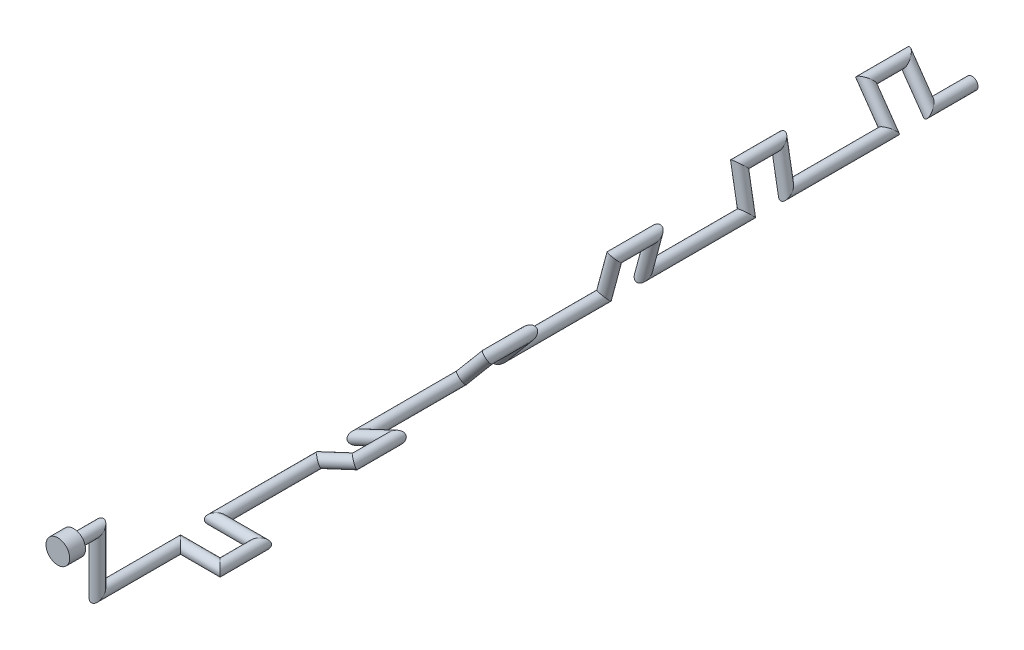
SolidWorks part; units mm, degrees
ref_plane "Front Plane" through (0, 0, 0) normal (0, 0, 1) x (1, 0, 0)
ref_plane "Top Plane" through (0, 0, 0) normal (0, 1, 0) x (1, 0, 0)
ref_plane "Right Plane" through (0, 0, 0) normal (1, 0, 0) x (0, 0, -1)
sketch "Sketch3" plane through (0, 0, 0) normal (0, 0, 1) x (1, 0, 0)
  circle A0 centre (0, 177.8) radius 38.1
  dimension "D1" = 76.2
  dimension "D2" = 177.8
extrude "Boss-Extrude2" add sketch "Sketch3" along normal blind 50.8
sketch "Sketch4" plane through (0, 0, 0) normal (0, 0, -1) x (-1, 0, 0)
  circle A0 centre (0, 177.8) radius 19.05
  dimension "D1" = 38.1
sketch3d "3DSketch1"
  line L0 (0, 177.8, 0) -> (0, 177.8, -76.2)
  line L1 (0, 177.8, 50.8) -> (0, 177.8, 0) construction
  line L2 (0, 0, -76.2) -> (0, 0, -177.8)
  line L4 (0, 177.8, -76.2) -> (0, 0, -76.2)
  dimension "D1" = 76.2
  dimension "D2" = 101.6
sweep "Sweep1" add profiles "Sketch4" path "3DSketch1"
fillet "Fillet1" radius 12.7 1 edges at (-19.05, 177.8, 0)
sketch3d "3DSketch2"
  line L0 (0, 0, -177.8) -> (0, 0, -342.9)
  line L1 (0, 0, -95.25) -> (0, 0, -177.8) construction
  line L2 (0, 0, -342.9) -> (127, 0, -342.9)
  line L3 (0, 0, -342.9) -> (156.6393, 0, -342.9) construction
  line L4 (127, 0, -342.9) -> (127, 0, -469.9)
  line L8 (127, 0, -469.9) -> (-12.7, 0, -469.9)
  line L9 (-12.7, 0, -469.9) -> (-12.7, 0, -800.1)
  line L14 (-12.7, 0, -800.1) -> (102.4011, 53.6699, -800.6318)
  line L15 (-12.7, 0, -800.1) -> (94.1188, 0, -800.1) construction
  line L16 (102.4011, 53.6699, -800.6318) -> (102.4011, 53.6699, -927.6318)
  line L18 (-12.7, 0, -800.1) -> (-12.7, 0, -4505.9984) construction
  line L20 (-12.7, 0, -927.1) -> (102.4011, 53.6699, -927.6318)
  line L21 (-12.7, 0, -927.1) -> (83.0144, 0, -927.1) construction
  line L22 (-12.7, 0, -927.1) -> (-12.7, 0, -1257.3)
  line L26 (-12.7, 0, -1257.3) -> (68.934, 97.2829, -1258.261)
  line L30 (-12.7, 0, -1257.3) -> (94.9072, 0, -1257.3) construction
  line L31 (68.934, 97.2829, -1258.261) -> (68.934, 97.2829, -1385.261)
  line L33 (-12.7, 0, -1384.3) -> (68.934, 97.2829, -1385.261)
  line L35 (-12.7, 0, -1384.3) -> (61.5526, 0, -1384.3) construction
  line L36 (-12.7, 0, -1384.3) -> (-12.7, 0, -1714.5)
  line L38 (-12.7, 0, -1714.5) -> (20.17, 122.6726, -1714.5)
  line L39 (-12.7, 0, -1714.5) -> (48.5088, 0, -1714.5) construction
  line L40 (20.17, 122.6726, -1714.5) -> (20.17, 122.6726, -1841.5)
  line L41 (-12.7, 0, -1841.5) -> (20.17, 122.6726, -1841.5)
  line L42 (-12.7, 0, -1841.5) -> (-12.7, 0, -2171.7)
  line L43 (-12.7, 0, -2171.7) -> (-34.7533, 125.0706, -2171.7)
  line L44 (-12.7, 0, -2171.7) -> (119.0895, 0, -2171.7) construction
  line L45 (-34.7533, 125.0706, -2171.7) -> (-34.7533, 125.0706, -2298.7)
  line L46 (-12.7, 0, -2298.7) -> (-34.7533, 125.0706, -2298.7)
  line L47 (-12.7, 0, -2298.7) -> (-12.7, 0, -2628.9)
  line L48 (-12.7, 0, -2628.9) -> (-85.5442, 104.0323, -2628.9)
  line L49 (-12.7, 0, -2628.9) -> (116.5073, 0, -2628.9) construction
  line L50 (-85.5442, 104.0323, -2628.9) -> (-85.5442, 104.0323, -2755.9)
  line L51 (-12.7, 0, -2755.9) -> (-85.5442, 104.0323, -2755.9)
  line L52 (-12.7, 0, -2755.9) -> (-12.7, 0, -2895.6)
  dimension "D33" = 165.1
  dimension "D2" = 127
  dimension "D3" = 0
  dimension "D4" = 127
  dimension "D5" = 139.7
  dimension "D7" = 127
  dimension "D6" = 330.2
  dimension "D8" = 25
  dimension "D32" = 127
  dimension "D9" = 127
  dimension "D10" = 127
  dimension "D11" = 25
  dimension "D12" = 330.2
  dimension "D13" = 50
  dimension "D14" = 127
  dimension "D15" = 127
  dimension "D16" = 50
  dimension "D28" = 127
  dimension "D17" = 139.7
  dimension "D18" = 127
  dimension "D19" = 75
  dimension "D31" = 127
  dimension "D20" = 127
  dimension "D21" = 127
  dimension "D22" = 330.2
  dimension "D23" = 127
  dimension "D24" = 100
  dimension "D25" = 127
  dimension "D26" = 127
  dimension "D27" = 330.2
  dimension "D29" = 125
  dimension "D30" = 127
  dimension "16" = 330.2
sketch "Sketch5" plane through (0, 0, -177.8) normal (0, 0, -1) x (-1, 0, 0)
  circle A0 centre (0, 0) radius 19.05
  dimension "D1" = 38.1
sweep "Sweep2" add profiles "Sketch5" path "3DSketch2"
